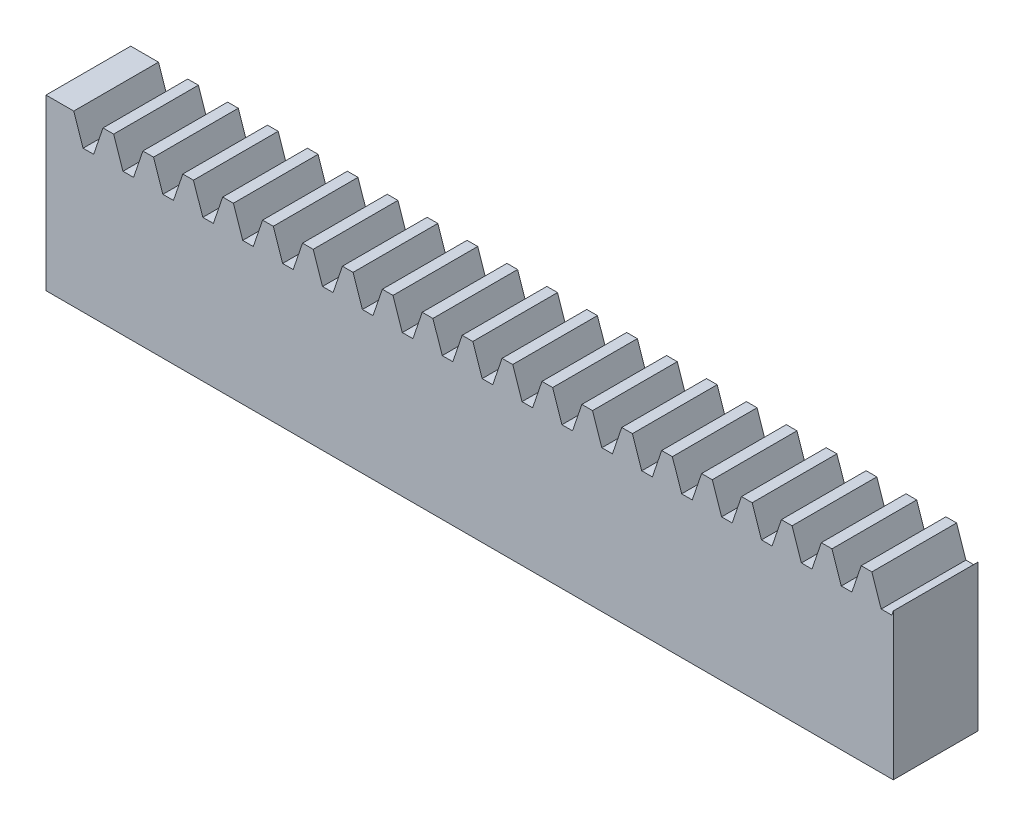
SolidWorks part; units mm, degrees
ref_plane "Alzado" through (0, 0, 0) normal (0, 0, 1) x (1, 0, 0)
ref_plane "Planta" through (0, 0, 0) normal (0, 1, 0) x (1, 0, 0)
ref_plane "Vista lateral" through (0, 0, 0) normal (1, 0, 0) x (0, 0, -1)
sketch "Croquis1" plane through (0, 0, 0) normal (0, 0, 1) x (1, 0, 0)
  line L1 (50, -10) -> (-50, -10)
  line L2 (50, -10) -> (50, 10)
  line L3 (50, 10) -> (-50, 10)
  line L4 (-50, -10) -> (-50, 10)
  line L5 (50, -10) -> (-50, 10) construction
  line L6 (50, 10) -> (-50, -10) construction
  point P0 (0, 0)
  dimension "D1" = 20
  dimension "D2" = 100
extrude "Saliente-Extruir1" add sketch "Croquis1" along normal blind 10
sketch "Croquis2" plane through (0, 0, 10) normal (0, 0, 1) x (1, 0, 0)
  line L0 (-43.275, 10) -> (-44.375, 6.75)
  line L1 (-44.375, 6.75) -> (-45.625, 6.75)
  line L2 (-45.625, 6.75) -> (-46.725, 10)
  line L3 (-46.725, 10) -> (-43.275, 10)
  line L4 (-45, 6.75) -> (-45, 10) construction
  line L5 (50, 10) -> (-50, 10) construction
  line L6 (-50, 10) -> (-50, -10) construction
  line L7 (-46.175, 8.375) -> (-43.825, 8.375) construction
  dimension "D1" = 5
  dimension "D2" = 3.25
  dimension "D3" = 1.625
  dimension "D4" = 2.35
  dimension "D5" = 1.25
extrude "Cortar-Extruir1" cut sketch "Croquis2" against normal through all
pattern_linear "MatrizL1" count 69 spacing 4.71 along (1, 0, 0) of "Cortar-Extruir1"
